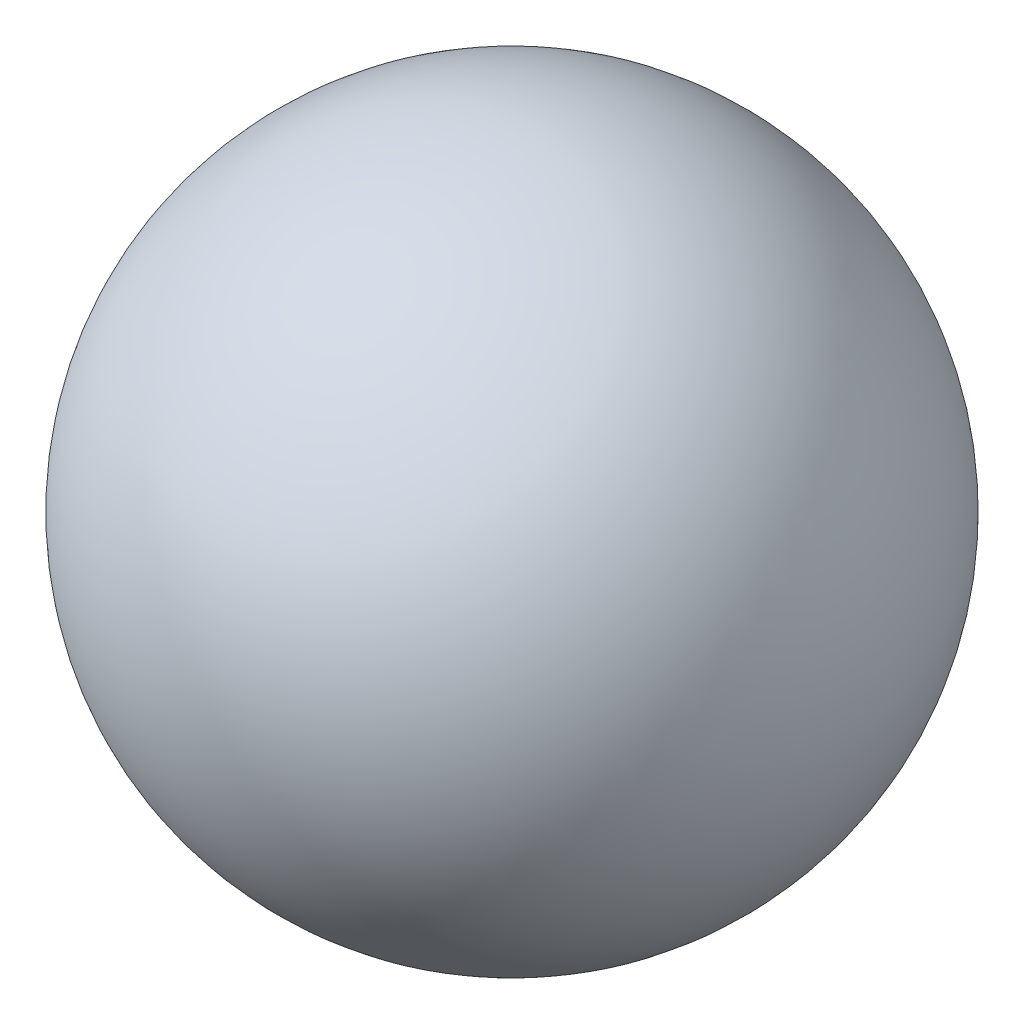
SolidWorks part; units mm, degrees
ref_plane "Alzado" through (0, 0, 0) normal (0, 0, 1) x (1, 0, 0)
ref_plane "Planta" through (0, 0, 0) normal (0, 1, 0) x (1, 0, 0)
ref_plane "Vista lateral" through (0, 0, 0) normal (1, 0, 0) x (0, 0, -1)
sketch "Croquis1" plane through (0, 0, 0) normal (1, 0, 0) x (0, 0, -1)
  line L0 (0, 88.9) -> (0, -88.9)
  arc A0 (0, 88.9) -> (0, -88.9) centre (0, 0) ccw
  dimension "D1" = 177.8
revolve "Revolución1" add sketch "Croquis1" angle 360 about L0
